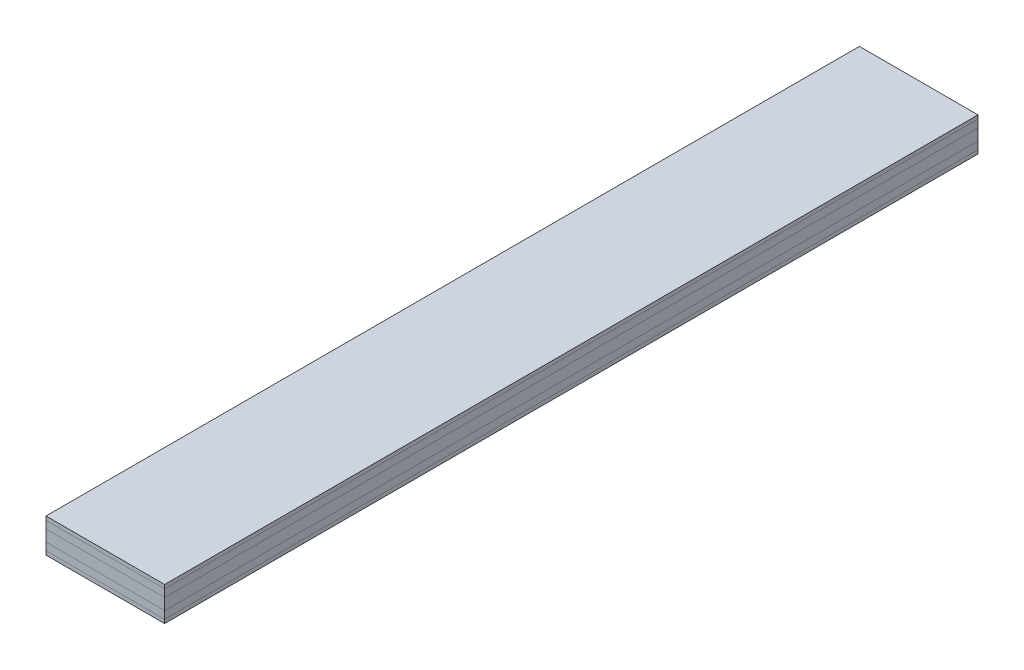
SolidWorks part; units mm, degrees
ref_plane "Front Plane" through (0, 0, 0) normal (0, 0, 1) x (1, 0, 0)
ref_plane "Top Plane" through (0, 0, 0) normal (0, 1, 0) x (1, 0, 0)
ref_plane "Right Plane" through (0, 0, 0) normal (1, 0, 0) x (0, 0, -1)
sketch "Sketch1" plane through (0, 0, 0) normal (0, 1, 0) x (1, 0, 0)
  line L0 (-304.8, 609.6) -> (304.8, 609.6) construction
  line L1 (304.8, 609.6) -> (304.8, -609.6) construction
  line L2 (0, 609.6) -> (0, 0) construction
  line L3 (0, 0) -> (304.8, 0) construction
  dimension "Width" = 609.6
  dimension "Length" = 1219.2
sketch "Sketch2" plane through (0, 0, 0) normal (1, 0, 0) x (0, 0, -1)
  line L0 (609.6, 0) -> (609.6, -25.4) construction
  dimension "Thickness" = 25.4
sketch "Sketch3" plane through (0, 0, 0) normal (0, 1, 0) x (1, 0, 0)
  line L1 (-304.8, 609.6) -> (304.8, 609.6)
  line L2 (-304.8, 609.6) -> (-304.8, -609.6)
  line L3 (-304.8, -609.6) -> (304.8, -609.6)
  line L4 (304.8, 609.6) -> (304.8, -609.6)
extrude "Boss-Extrude1" add sketch "Sketch3" against normal up to vertex (25.4 mm away) up to point (0, -25.4, -609.6)
sketch "Sketch4" plane through (0, 0, 0) normal (0, 0, 1) x (1, 0, 0)
  line L0 (0, -11.2889) -> (0, -14.1111) construction
  line L1 (-335.28, -22.5778) -> (335.28, -22.5778)
  line L2 (0, 0) -> (0, -25.4) construction
  line L3 (0, -11.2889) -> (0, -8.4667) construction
  line L4 (0, -14.1111) -> (0, -16.9333) construction
  line L5 (0, -8.4667) -> (0, -5.6444) construction
  line L6 (0, -5.6444) -> (0, -2.8222) construction
  line L7 (0, -2.8222) -> (0, 0) construction
  line L8 (0, -16.9333) -> (0, -19.7556) construction
  line L9 (0, -19.7556) -> (0, -22.5778) construction
  line L10 (0, -22.5778) -> (0, -25.4) construction
  line L11 (-335.28, -16.9333) -> (335.28, -16.9333)
  line L12 (-335.28, -2.8222) -> (335.28, -2.8222)
  line L13 (-335.28, -8.4667) -> (335.28, -8.4667)
  point P5 (0, -12.7)
  point P16 (0, -22.5778)
  point P19 (0, -16.9333)
  point P23 (0, -2.8222)
  point P25 (0, -8.4667)
  dimension "D1" = 670.56
split "Split1" trim tools "Sketch4" bodies to split 104 resulting bodies 105 106 107 108 109
sketch "Sketch6" plane through (0, 0, 0) normal (0, 1, 0) x (1, 0, 0)
  line L1 (-304.8, -609.6) -> (304.8, -609.6) construction
  line L2 (215.9, -609.6) -> (215.9, 0)
  line L3 (215.9, 0) -> (304.8, 0)
  line L4 (304.8, -609.6) -> (304.8, 609.6) construction
  line L6 (-304.8, 609.6) -> (-304.8, -609.6)
  line L7 (-304.8, -609.6) -> (304.8, -609.6)
  line L8 (304.8, -609.6) -> (304.8, 609.6)
  line L9 (304.8, 609.6) -> (-304.8, 609.6)
  line M9 (-304.8, 609.6) -> (-304.8, -609.6)
  line M10 (-304.8, -609.6) -> (304.8, -609.6)
  line M11 (304.8, -609.6) -> (304.8, 609.6)
  line M12 (304.8, 609.6) -> (-304.8, 609.6)
extrude "Cut-Extrude1" cut sketch "Sketch6" against normal blind 25.4 contours L2 L3 M11 M12 M9 M10
equation "\"D1@Sketch4\"=\"Width@Sketch1\"*1.1"
